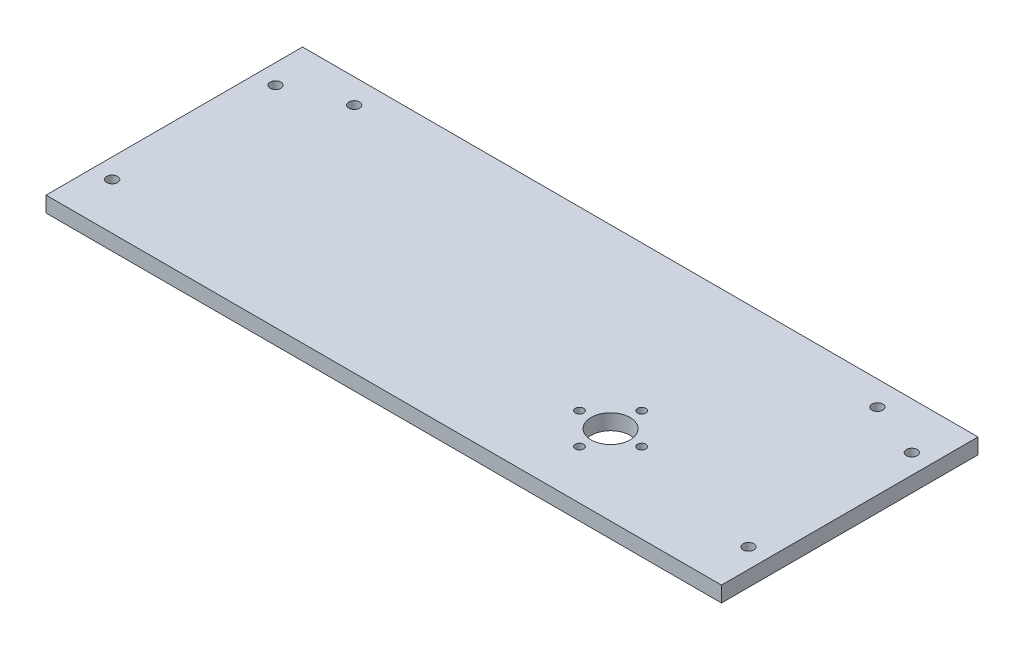
SolidWorks part; units mm, degrees
ref_plane "Front Plane" through (0, 0, 0) normal (0, 0, 1) x (1, 0, 0)
ref_plane "Top Plane" through (0, 0, 0) normal (0, 1, 0) x (1, 0, 0)
ref_plane "Right Plane" through (0, 0, 0) normal (1, 0, 0) x (0, 0, -1)
sketch "Sketch1" plane through (0, 0, 0) normal (0, 1, 0) x (1, 0, 0)
  line L1 (-138, 52.413) -> (138, 52.413)
  line L2 (-138, 52.413) -> (-138, -52.413)
  line L3 (-138, -52.413) -> (138, -52.413)
  line L4 (138, 52.413) -> (138, -52.413)
  line L5 (-138, 52.413) -> (138, -52.413) construction
  line L6 (-138, -52.413) -> (138, 52.413) construction
  point P0 (0, 0)
  dimension "D1" = 276
  dimension "D2" = 104.826
extrude "Boss-Extrude1" add sketch "Sketch1" along normal blind 6.35
sketch "Sketch2" plane through (0, 6.35, 0) normal (0, 1, 0) x (1, 0, 0)
  line L0 (138, 52.413) -> (-138, 52.413) construction
  line L1 (-138, -52.413) -> (138, -52.413) construction
  line L2 (0, -3.4925) -> (0, 3.4925) construction
  circle A0 centre (-130, 33.363) radius 2.2
  circle A1 centre (-130, -33.363) radius 2.2
  circle A2 centre (130, -33.363) radius 2.2
  circle A3 centre (130, 33.363) radius 2.2
  dimension "D1" = 4.4
  dimension "D2" = 19.05
  dimension "D3" = 19.05
  dimension "D4" = 260
extrude "Cut-Extrude1" cut sketch "Sketch2" against normal up to next
sketch "Sketch3" plane through (0, 6.35, 0) normal (0, 1, 0) x (1, 0, 0)
  line L0 (138, 52.413) -> (-138, 52.413) construction
  line L1 (-138, 52.413) -> (-138, -52.413) construction
  line L2 (138, -52.413) -> (138, 52.413) construction
  circle A0 centre (-106.885, 42.413) radius 2.2
  circle A1 centre (106.885, 42.413) radius 2.2
  dimension "D2" = 4.4
  dimension "D1" = 10
  dimension "D3" = 31.115
  dimension "D4" = 31.115
extrude "Cut-Extrude2" cut sketch "Sketch3" against normal up to next
sketch "Sketch4" plane through (0, 6.35, 0) normal (0, 1, 0) x (1, 0, 0)
  line L0 (138, -52.413) -> (138, 52.413) construction
  line L1 (-138, -52.413) -> (138, -52.413) construction
  circle A0 centre (60, -19.718) radius 7.9629
  dimension "D1" = 15.9258
  dimension "D2" = 78
  dimension "D3" = 32.695
extrude "Cut-Extrude3" cut sketch "Sketch4" against normal up to next
sketch "Sketch5" plane through (0, 6.35, 0) normal (0, 1, 0) x (1, 0, 0)
  line L0 (60, -19.718) -> (60, -7.018) construction
  circle A0 centre (60, -7.018) radius 1.7
  circle A2 centre (72.7, -19.718) radius 1.7
  circle A3 centre (60, -32.418) radius 1.7
  circle A4 centre (47.3, -19.718) radius 1.7
  point P13 (60, -19.718)
  dimension "D1" = 3.4
  dimension "D3" = 12.7
  dimension "D2" = 4
extrude "Cut-Extrude4" cut sketch "Sketch5" against normal up to next
equation "\"D4@Sketch3\"=\"D3@Sketch3\""
